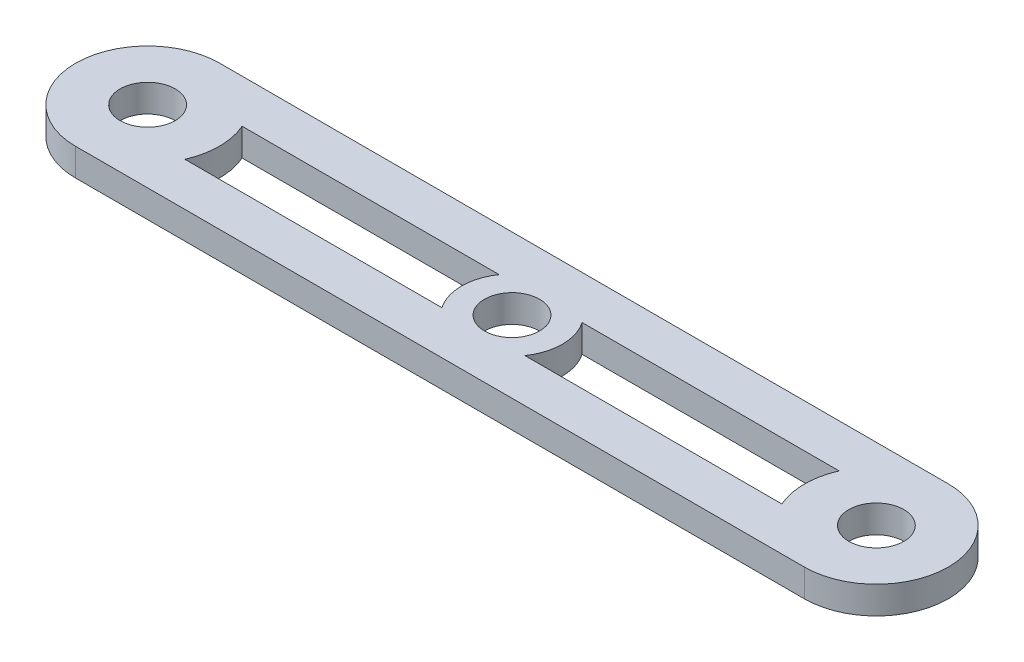
SolidWorks part; units mm, degrees
material "6061-T6 (SS)"
ref_plane "Front Plane" through (0, 0, 0) normal (0, 0, 1) x (1, 0, 0)
ref_plane "Top Plane" through (0, 0, 0) normal (0, 1, 0) x (1, 0, 0)
ref_plane "Right Plane" through (0, 0, 0) normal (1, 0, 0) x (0, 0, -1)
sketch "Sketch1" plane through (0, 0, 0) normal (0, 1, 0) x (1, 0, 0)
  line L0 (-21, 0) -> (21, 0) construction
  line L1 (21, 4.15) -> (-21, 4.15)
  line L2 (17.2028, 1.65) -> (2.3906, 1.65)
  line L3 (-21, -4.15) -> (21, -4.15)
  line L4 (-17.2028, -1.65) -> (-2.3906, -1.65)
  line L5 (-2.3906, 1.65) -> (-17.2028, 1.65)
  line L6 (21, 1.65) -> (-21, 1.65) construction
  line L7 (-21, -1.65) -> (21, -1.65) construction
  line L8 (2.3906, -1.65) -> (17.2028, -1.65)
  circle A0 centre (21, 0) radius 1.5875
  circle A1 centre (-21, 0) radius 1.5875
  arc A2 (-21, 4.15) -> (-21, -4.15) centre (-21, 0) ccw
  arc A3 (21, -4.15) -> (21, 4.15) centre (21, 0) ccw
  circle A4 centre (-9.4564, 0) radius 0.5953 construction
  circle A5 centre (-4.9564, 0) radius 0.5953 construction
  arc A6 (-17.2028, 1.65) -> (-17.2028, -1.65) centre (-21, 0) cw
  arc A7 (21, -1.65) -> (21, 1.65) centre (21, 0) ccw
  arc A8 (-21, 1.65) -> (-21, -1.65) centre (-21, 0) ccw construction
  arc A9 (17.2028, 1.65) -> (17.2028, -1.65) centre (21, 0) ccw
  circle A10 centre (0, 0) radius 1.5875
  arc A11 (-2.3906, 1.65) -> (-2.3906, -1.65) centre (0, 0) ccw
  arc A12 (2.3906, -1.65) -> (2.3906, 1.65) centre (0, 0) ccw
  point P3 (0, 0)
  dimension "D2" = 3.175
  dimension "D3" = 1.1906
  dimension "D4" = 4.5
  dimension "D1" = 42
  dimension "D5" = 2.5
  dimension "D6" = 8.3
extrude "Boss-Extrude2" add sketch "Sketch1" along normal mid plane 1.5875
sketch "Sketch2" plane through (0, -0.7937, 0) normal (0, -1, 0) x (-1, 0, 0)
  circle A0 centre (10.88, 0) radius 1.65
  point P0 (10.88, 0)
  point P1 (-21, 0)
  point P5 (0, 0)
  dimension "D1" = 31.88
